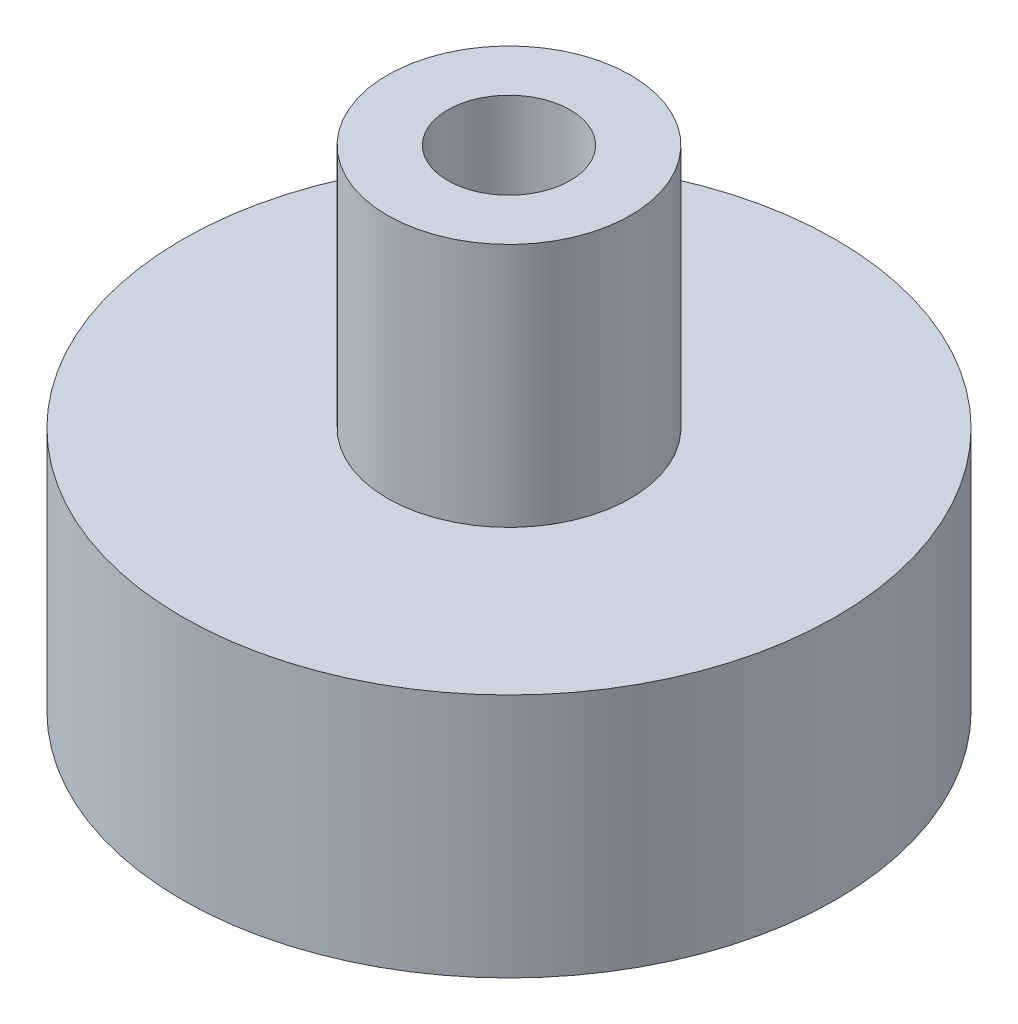
SolidWorks part; units mm, degrees
ref_plane "Front Plane" through (0, 0, 0) normal (0, 0, 1) x (1, 0, 0)
ref_plane "Top Plane" through (0, 0, 0) normal (0, 1, 0) x (1, 0, 0)
ref_plane "Right Plane" through (0, 0, 0) normal (1, 0, 0) x (0, 0, -1)
sketch "Sketch1" plane through (0, 0, 0) normal (0, 1, 0) x (1, 0, 0)
  circle A0 centre (-27.9181, -5.991) radius 2.3622 construction
  circle A1 centre (-27.9181, -5.991) radius 6.35
  circle A2 centre (-27.9181, -5.991) radius 1.1906
extrude "Boss-Extrude1" add sketch "Sketch1" along normal blind 4.7625
sketch "Sketch4" plane through (0, 0, 0) normal (0, 1, 0) x (1, 0, 0)
  circle A0 centre (-27.9181, -5.991) radius 2.3622
  circle A1 centre (-27.9181, -5.991) radius 1.1906
extrude "Boss-Extrude2" add sketch "Sketch4" along normal blind 9.525
